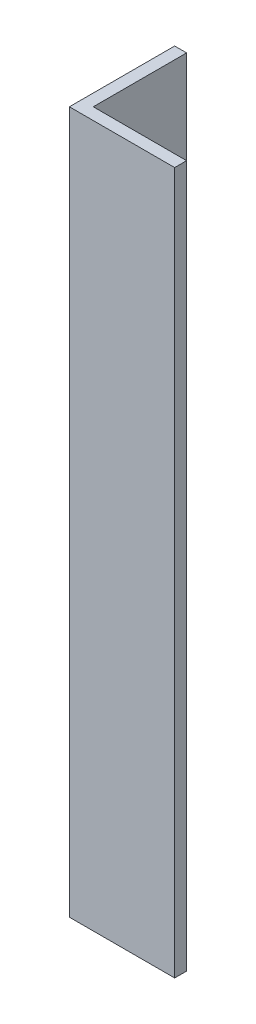
SolidWorks part; units mm, degrees
ref_plane "Front Plane" through (0, 0, 0) normal (0, 0, 1) x (1, 0, 0)
ref_plane "Top Plane" through (0, 0, 0) normal (0, 1, 0) x (1, 0, 0)
ref_plane "Right Plane" through (0, 0, 0) normal (1, 0, 0) x (0, 0, -1)
sketch "Sketch1" plane through (0, 0, 0) normal (0, 1, 0) x (1, 0, 0)
  line L0 (0, 0) -> (0, 30)
  line L1 (0, 0) -> (30, 0)
  line L2 (0, 30) -> (3.4, 30)
  line L3 (30, 0) -> (30, 3.4)
  line L6 (3.4, 30) -> (3.4, 3.4)
  line L7 (3.4, 3.4) -> (30, 3.4)
extrude "Boss-Extrude1" add sketch "Sketch1" along normal blind 200
